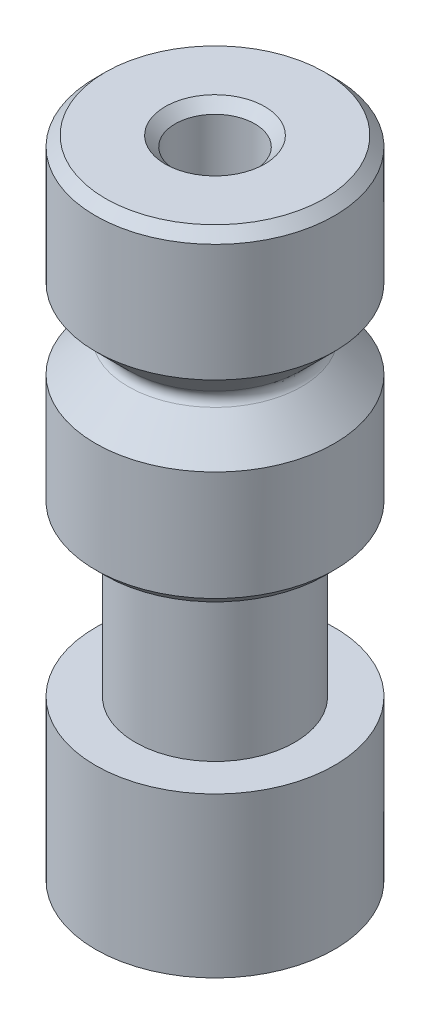
SolidWorks part; units mm, degrees
material "AISI 304"
ref_plane "Front Plane" through (0, 0, 0) normal (0, 0, 1) x (1, 0, 0)
ref_plane "Top Plane" through (0, 0, 0) normal (0, 1, 0) x (1, 0, 0)
ref_plane "Right Plane" through (0, 0, 0) normal (1, 0, 0) x (0, 0, -1)
sketch "Sketch1" plane through (0, 0, 0) normal (0, 0, 1) x (1, 0, 0)
  line L0 (0, 54.2) -> (0, -52.7176) construction
  line L1 (0, -55) -> (0, 55) construction
  line L2 (-1, 4.2) -> (-3, 4.2)
  line L3 (-3, 4.2) -> (-3, 1)
  line L4 (-3, 1) -> (-2, 0)
  line L5 (-2, 0) -> (-3, -1)
  line L6 (-3, -1) -> (-3, -4)
  line L8 (-16.4493, 0) -> (20.3045, 0) construction
  line L9 (-3, -4) -> (-2, -4)
  line L10 (-2, -4) -> (-2, -8)
  line L11 (-2, -13) -> (-1, -13)
  line L12 (0, 20.1534) -> (0, -21.359) construction
  line L13 (55, 0) -> (-55, 0) construction
  line L14 (-2, -8) -> (-3, -8)
  line L15 (-1, 4.2) -> (-1, -13)
  line L16 (-3, -8) -> (-3, -12)
  line L17 (-3, -12) -> (-2, -12)
  line L18 (-2, -12) -> (-2, -13)
  dimension "D1" = 6
  dimension "D2" = 6
  dimension "D3" = 4
  dimension "D4" = 17.2
  dimension "D5" = 4
  dimension "D6" = 4
  dimension "D7" = 2
  dimension "D8" = 1
  dimension "D9" = 1
  dimension "D10" = 1
  dimension "D11" = 4
revolve "Revolve1" add sketch "Sketch1" angle 360 about L0
chamfer "Chamfer1" distance 0.25 angle 45 1 edges at (0, 4.2, 1)
chamfer "Chamfer3" distance 0.5 angle 45 1 edges at (0, -13, 2)
chamfer "Chamfer4" distance 0.25 angle 45 2 edges at (0, 4.2, 3) (0, -4, 3)
fillet "Fillet1" radius 0.25 1 edges at (0, 0, 2)
